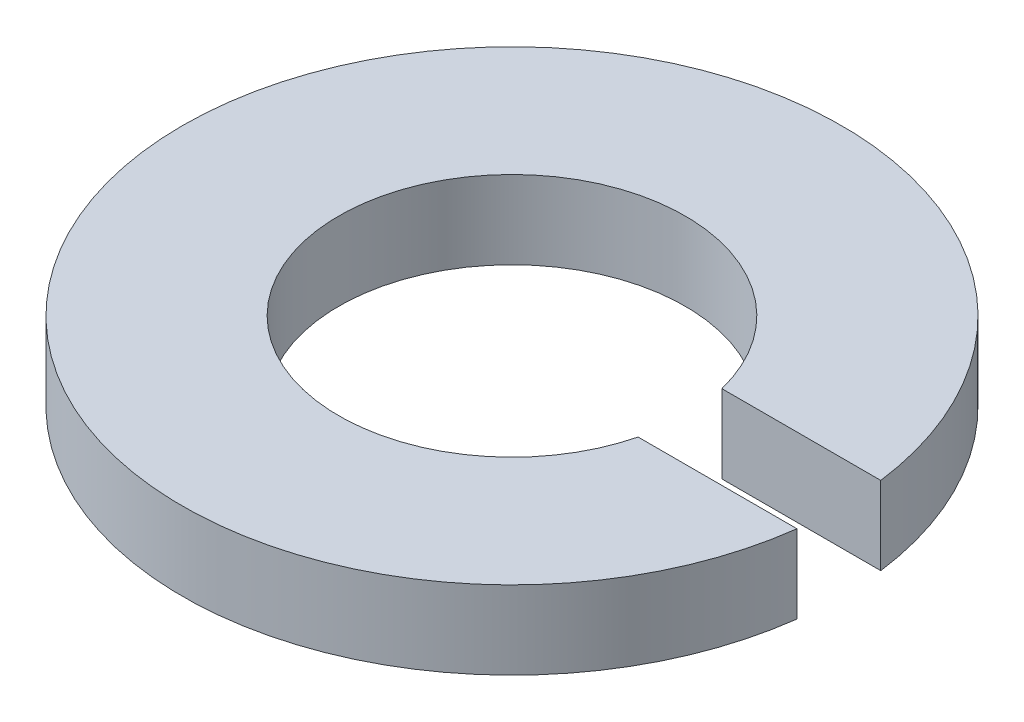
SolidWorks part; units mm, degrees
material "炭素鋼(普通)"
ref_plane "正面" through (0, 0, 0) normal (0, 0, 1) x (1, 0, 0)
ref_plane "平面" through (0, 0, 0) normal (0, 1, 0) x (1, 0, 0)
ref_plane "右側面" through (0, 0, 0) normal (1, 0, 0) x (0, 0, -1)
sketch "ｽｹｯﾁ1" plane through (0, 0, 0) normal (0, 1, 0) x (1, 0, 0)
  line L0 (0, 0) -> (2.95, 0) construction
  line L1 (1.504, 0.375) -> (2.9261, 0.375)
  line L2 (1.504, -0.375) -> (2.9261, -0.375)
  circle A0 centre (0, 0) radius 2.95
  circle A1 centre (0, 0) radius 1.55
  dimension "D1" = 5.9
  dimension "D2" = 3.1
  dimension "D3" = 0.75
extrude "ﾎﾞｽ - 押し出し1" add sketch "ｽｹｯﾁ1" along normal blind 0.7 contours A1 L1 A0 L2
